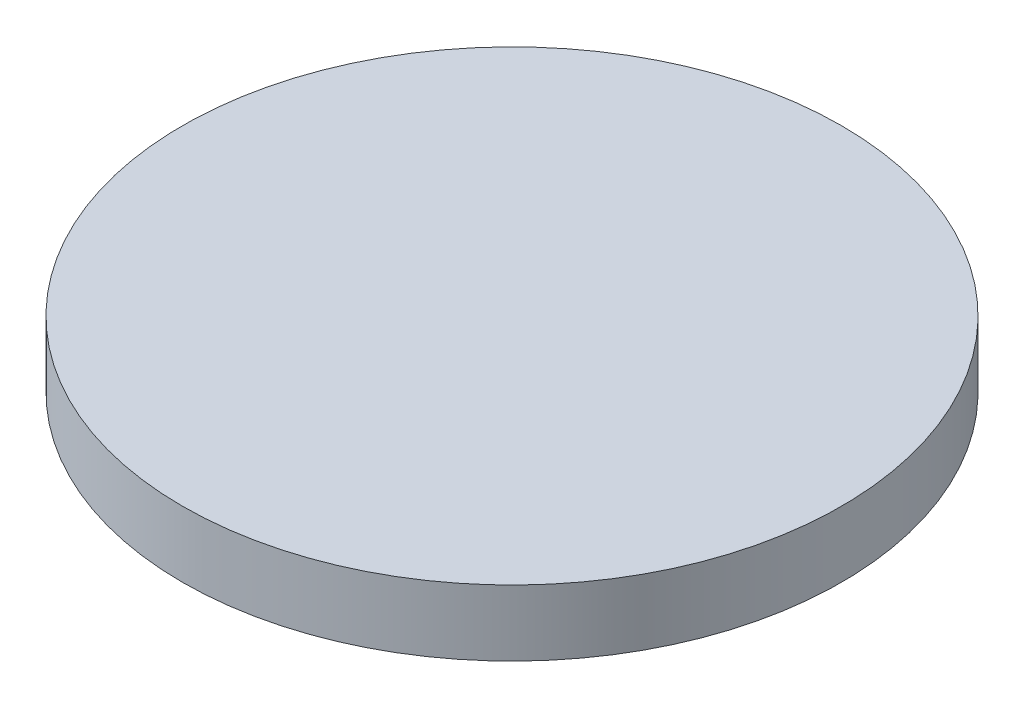
SolidWorks part; units mm, degrees
ref_plane "Front Plane" through (0, 0, 0) normal (0, 0, 1) x (1, 0, 0)
ref_plane "Top Plane" through (0, 0, 0) normal (0, 1, 0) x (1, 0, 0)
ref_plane "Right Plane" through (0, 0, 0) normal (1, 0, 0) x (0, 0, -1)
sketch "Sketch1" plane through (0, 0, 0) normal (0, 1, 0) x (1, 0, 0)
  circle A0 centre (0, 0) radius 95.25
  dimension "D1" = 190.5
extrude "Boss-Extrude1" add sketch "Sketch1" along normal blind 19.05
